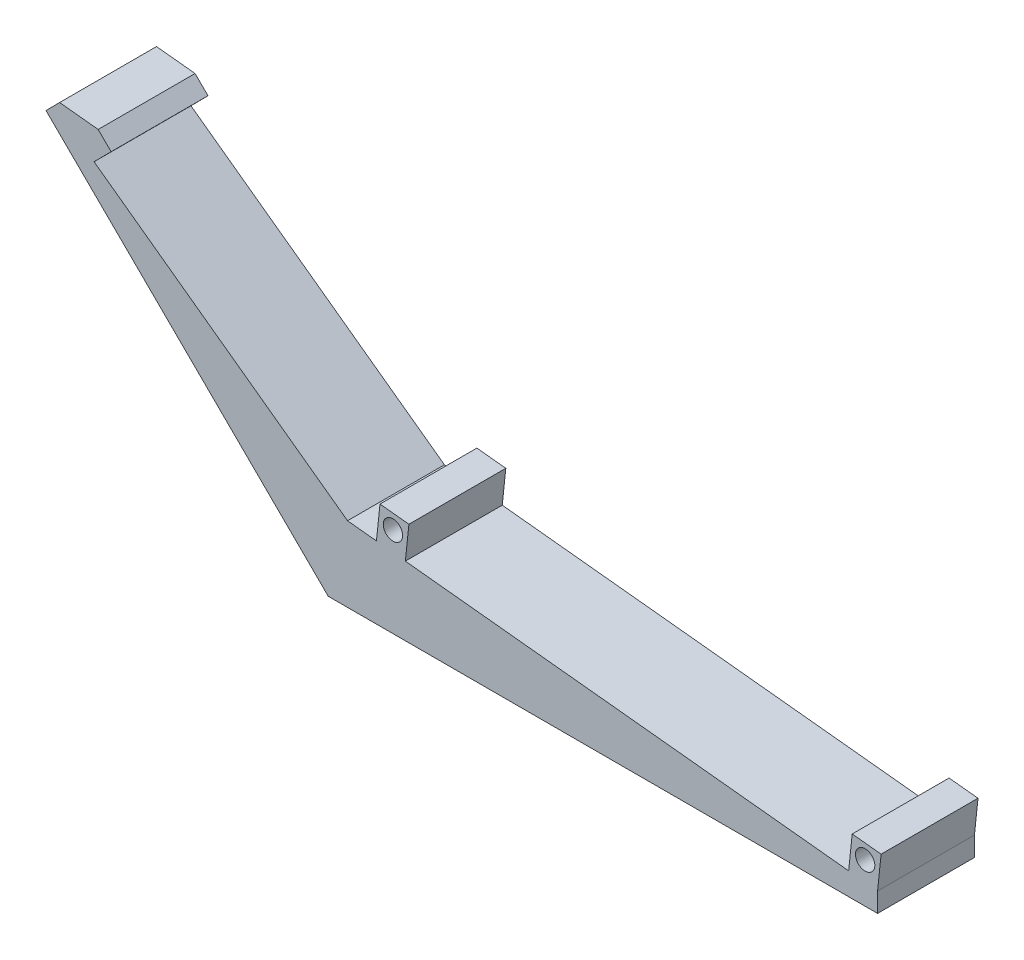
SolidWorks part; units mm, degrees
material "6061 Alloy"
ref_plane "Front Plane" through (0, 0, 0) normal (0, 0, 1) x (1, 0, 0)
ref_plane "Top Plane" through (0, 0, 0) normal (0, 1, 0) x (1, 0, 0)
ref_plane "Right Plane" through (0, 0, 0) normal (1, 0, 0) x (0, 0, -1)
sketch "Sketch1" plane through (0, 0, 0) normal (0, 0, 1) x (1, 0, 0)
  line L0 (0, 0) -> (56.6867, 0)
  line L1 (56.6867, 0) -> (56.6867, 2)
  line L2 (53.7031, 2.3136) -> (7.9551, 7.1219)
  line L3 (1.988, 7.7491) -> (-24.1704, 26.7543)
  line L4 (-24.1704, 26.7543) -> (-21.3556, 29.5962) construction
  line L5 (-21.3556, 29.5962) -> (-24.9081, 33.1147) construction
  line L6 (-24.9081, 33.1147) -> (-29.1303, 28.8518) construction
  line L7 (-29.1303, 28.8518) -> (0, 0)
  line L8 (53.7031, 2.3136) -> (53.9122, 4.3026)
  line L9 (56.8957, 3.989) -> (56.6867, 2)
  line L10 (4.9715, 7.4355) -> (5.1806, 9.4245)
  line L11 (8.1641, 9.1109) -> (7.9551, 7.1219)
  line L12 (4.9715, 7.4355) -> (1.988, 7.7491)
  line L14 (-29.1303, 28.8518) -> (-27.7245, 30.2711)
  line L15 (-27.7245, 30.2711) -> (-23.7465, 29.853)
  line L16 (-23.7465, 29.853) -> (-22.4112, 28.5305)
  line L17 (-24.1704, 26.7543) -> (-22.4112, 28.5305)
  line L18 (5.1806, 9.4245) -> (5.3374, 10.9163)
  line L19 (5.3374, 10.9163) -> (8.3209, 10.6027)
  line L20 (8.3209, 10.6027) -> (8.1641, 9.1109)
  line L21 (53.9122, 4.3026) -> (54.0689, 5.7944)
  line L22 (54.0689, 5.7944) -> (57.0525, 5.4808)
  line L23 (57.0525, 5.4808) -> (56.8957, 3.989)
  arc A0 (53.9122, 4.3026) -> (56.8957, 3.989) centre (55.4039, 4.1458) cw construction
  circle A1 centre (55.4039, 4.1458) radius 1
  arc A2 (5.1806, 9.4245) -> (8.1641, 9.1109) centre (6.6724, 9.2677) cw construction
  circle A3 centre (6.6724, 9.2677) radius 1
  dimension "D10" = 1.5
  dimension "D12" = 2
  dimension "D14" = 1.5
  dimension "D16" = 2
  dimension "D1" = 2
  dimension "D2" = 8
  dimension "D3" = 55
  dimension "D4" = 2
  dimension "D5" = 150
  dimension "D6" = 5
  dimension "D7" = 6
  dimension "D8" = 41
  dimension "D9" = 6
  dimension "D11" = 2
  dimension "D13" = 2.3136
  dimension "D15" = 2
  dimension "D17" = 3
  dimension "D18" = 4
  dimension "D19" = 2.5
extrude "Boss-Extrude1" add sketch "Sketch1" along normal blind 10
